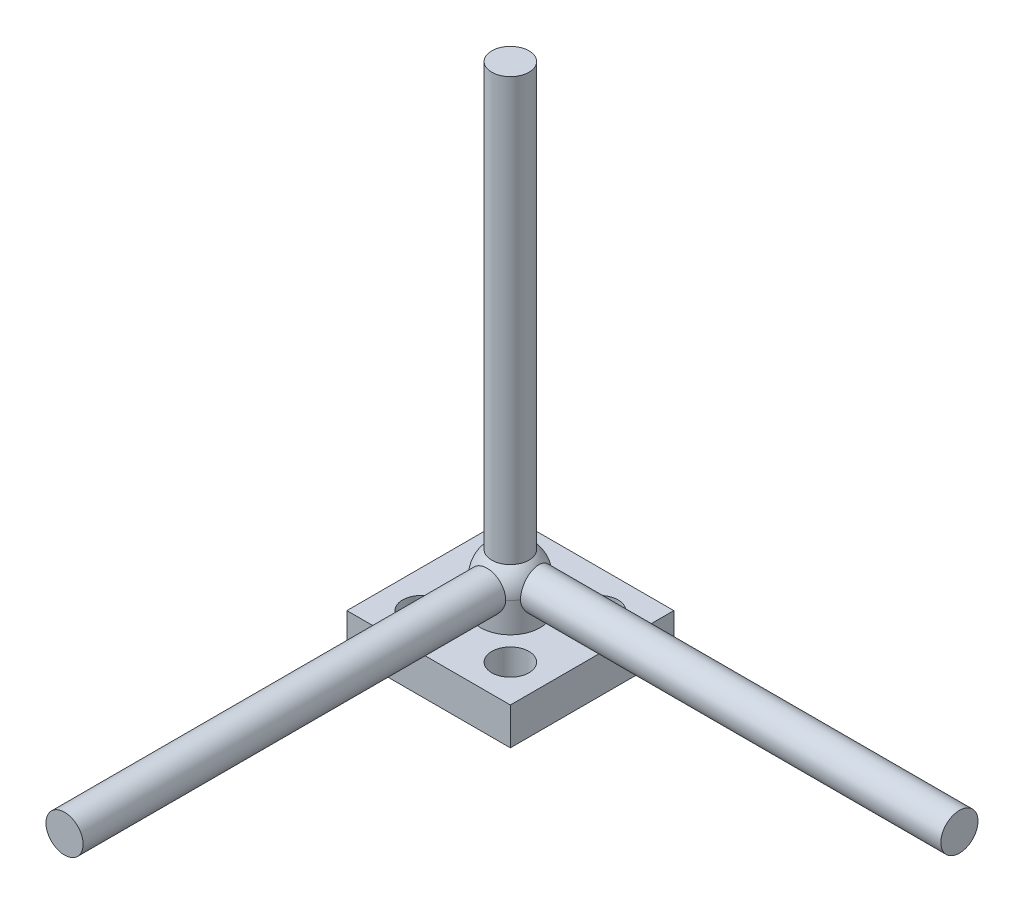
SolidWorks part; units mm, degrees
ref_plane "前视基准面" through (0, 0, 0) normal (0, 0, 1) x (1, 0, 0)
ref_plane "上视基准面" through (0, 0, 0) normal (0, 1, 0) x (1, 0, 0)
ref_plane "右视基准面" through (0, 0, 0) normal (1, 0, 0) x (0, 0, -1)
other "Configuration Table"
sketch "草图1" plane through (0, 0, 0) normal (0, 1, 0) x (1, 0, 0)
  line L1 (-11, -11) -> (11, -11)
  line L2 (-11, -11) -> (-11, 11)
  line L3 (-11, 11) -> (11, 11)
  line L4 (11, -11) -> (11, 11)
  line L5 (-11, -11) -> (11, 11) construction
  line L6 (-11, 11) -> (11, -11) construction
  line L7 (-6, -6) -> (6, -6) construction
  line L8 (-6, -6) -> (-6, 6) construction
  line L9 (-6, 6) -> (6, 6) construction
  line L10 (6, -6) -> (6, 6) construction
  line L11 (-6, -6) -> (6, 6) construction
  line L12 (-6, 6) -> (6, -6) construction
  circle A0 centre (-6, 6) radius 2.5
  circle A1 centre (6, 6) radius 2.5
  circle A2 centre (-6, -6) radius 2.5
  circle A3 centre (6, -6) radius 2.5
  point P0 (0, 0)
  point P6 (0, 0)
  dimension "D4" = 5
  dimension "D5" = 5
  dimension "D6" = 5
  dimension "D7" = 5
  dimension "D1" = 22
  dimension "D2" = 22
  dimension "D3" = 12
extrude "凸台-拉伸2" add sketch "草图1" along normal blind 5
sketch "草图3" plane through (0, 0, 0) normal (0, 1, 0) x (1, 0, 0)
  circle A0 centre (0, 0) radius 4
  dimension "D1" = 8
extrude "凸台-拉伸3" add sketch "草图3" along normal blind 4 from surface at 5 starting at face at (0, 5, 0)
sketch "草图4" plane through (0, 0, 0) normal (0, 0, 1) x (1, 0, 0)
  line L0 (0, -1000) -> (0, 49000) construction
  line L1 (4, 9) -> (-4, 9) construction
  line L2 (0, 13) -> (0, 5)
  arc A0 (0, 5) -> (0, 13) centre (0, 9) ccw
revolve "旋转1" add sketch "草图4" angle 360 about L0
sketch "草图5" plane through (0, 0, 0) normal (0, 1, 0) x (1, 0, 0)
  circle A0 centre (0, 0) radius 2.5
  dimension "D1" = 5
extrude "凸台-拉伸4" add sketch "草图5" along normal blind 64 from surface at 5 starting at face at (0, 5, -4)
sketch "草图6" plane through (0, 0, 0) normal (0, 0, 1) x (1, 0, 0)
  line L0 (4, 9) -> (-4, 9) construction
  circle A0 centre (0, 9) radius 2.5
  dimension "D1" = 5
extrude "凸台-拉伸5" add sketch "草图6" along normal blind 60
sketch "草图7" plane through (0, 0, 0) normal (1, 0, 0) x (0, 0, -1)
  line L0 (-3.1225, 9) -> (4, 9) construction
  circle A0 centre (0.4388, 9) radius 2.5
  dimension "D1" = 5
extrude "凸台-拉伸6" add sketch "草图7" along normal blind 60
